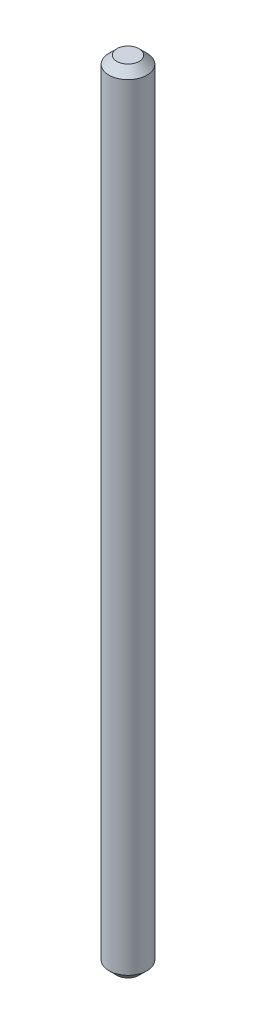
SolidWorks part; units mm, degrees
ref_plane "Front" through (0, 0, 0) normal (0, 0, 1) x (1, 0, 0)
ref_plane "Top" through (0, 0, 0) normal (0, 1, 0) x (1, 0, 0)
ref_plane "Right" through (0, 0, 0) normal (1, 0, 0) x (0, 0, -1)
sketch "Sketch1" plane through (0, 0, 0) normal (0, 1, 0) x (1, 0, 0)
  circle A0 centre (0, 0) radius 3.048
  dimension "D1" = 6.096
extrude "Boss-Extrude1" add sketch "Sketch1" along normal blind 127
chamfer "Chamfer1" distance 1.27 angle 45 1 edges at (0, 127, 3.048)
chamfer "Chamfer2" distance 1.27 angle 45 1 edges at (0, 0, 3.048)
